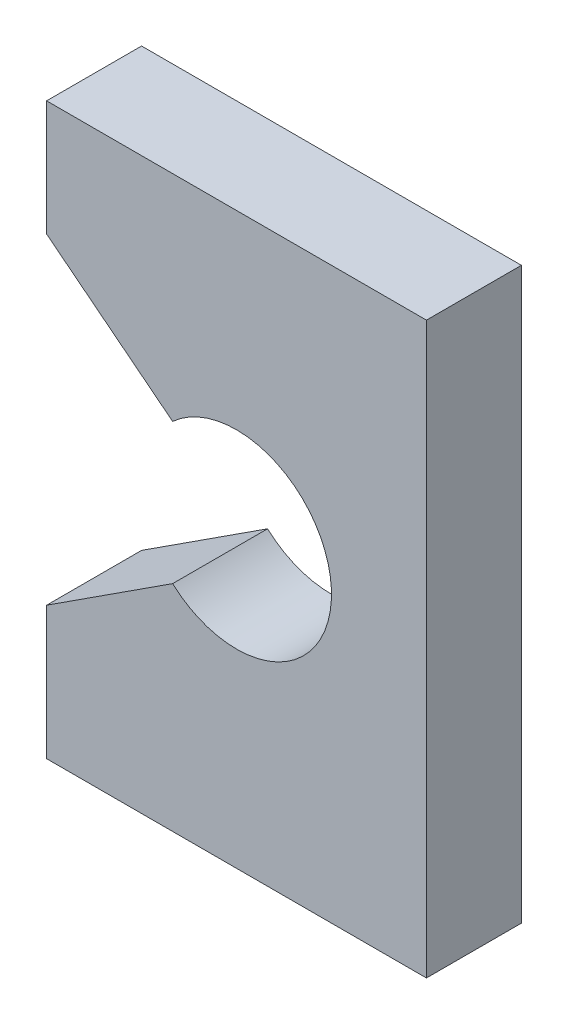
SolidWorks part; units mm, degrees
ref_plane "Plan de face" through (0, 0, 0) normal (0, 0, 1) x (1, 0, 0)
ref_plane "Plan de dessus" through (0, 0, 0) normal (0, 1, 0) x (1, 0, 0)
ref_plane "Plan de droite" through (0, 0, 0) normal (1, 0, 0) x (0, 0, -1)
sketch "Esquisse1" plane through (0, 0, 0) normal (0, 0, 1) x (1, 0, 0)
  line L0 (-10, 15) -> (-10, 8.925)
  line L1 (-10, 15) -> (10, 15)
  line L3 (-10, -15) -> (10, -15)
  line L4 (10, 15) -> (10, -15)
  line L7 (-10, -8) -> (-10, -15)
  line L10 (-10, -8) -> (-3.3648, -3.6984)
  line L11 (-10, 8.925) -> (-3.3648, 3.6984)
  arc A0 (-3.3648, 3.6984) -> (-3.3648, -3.6984) centre (0, 0) cw
  point P10 (0, 0)
  point P11 (-3.4991, 3.5716)
  point P12 (-3.4991, -3.4142)
  point P13 (-3.0796, 4.0029)
  point P14 (0, 0)
  point P15 (0, 0)
  point P17 (-12.2583, -20.6327)
  dimension "D3" = 5
  dimension "D1" = 30
  dimension "D2" = 20
  dimension "D4" = 10
  dimension "D5" = 15
  dimension "D6" = 7
extrude "Boss.-Extru.1" add sketch "Esquisse1" along normal blind 5 contours A0 L10 L7 L3 L4 L1 L0 L11
